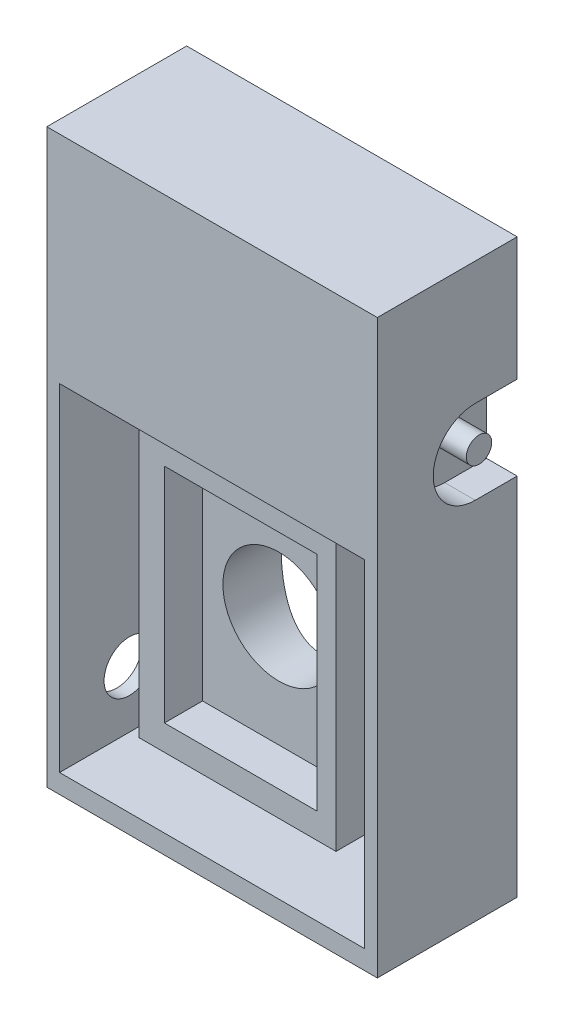
SolidWorks part; units mm, degrees
ref_plane "Front Plane" through (0, 0, 0) normal (0, 0, 1) x (1, 0, 0)
ref_plane "Top Plane" through (0, 0, 0) normal (0, 1, 0) x (1, 0, 0)
ref_plane "Right Plane" through (0, 0, 0) normal (1, 0, 0) x (0, 0, -1)
sketch "Sketch1" plane through (0, 0, 0) normal (0, 0, 1) x (1, 0, 0)
  line L1 (0, 0) -> (26, 0)
  line L2 (0, 0) -> (0, -45)
  line L3 (0, -45) -> (26, -45)
  line L4 (26, 0) -> (26, -45)
  dimension "D1" = 45
  dimension "D2" = 26
extrude "Boss-Extrude1" add sketch "Sketch1" along normal blind 11
sketch "Sketch2" plane through (0, -45, 0) normal (0, -1, 0) x (1, 0, 0)
  line L0 (0, 0) -> (26, 0) construction
  line L1 (7, 0) -> (19, 0) construction
  line L2 (13, 2.5) -> (13, 0) construction
  circle A0 centre (13, -5.95) radius 8.45
  point P5 (13, 0)
  dimension "D1" = 2.5
  dimension "D2" = 12
extrude "Cut-Extrude1" cut sketch "Sketch2" against normal blind 28
ref_plane "Plane1" through (0, -43.5, 0) normal (0, -1, 0) x (-1, 0, 0)
sketch "Sketch4" plane through (0, -43.5, 0) normal (0, -1, 0) x (-1, 0, 0)
  line L0 (-1, -11) -> (-1, -1)
  line L1 (-1, -1) -> (-6.5969, -1)
  line L2 (-19.4031, -1) -> (-25, -1)
  line L3 (-25, -1) -> (-25, -11)
  line L4 (-1, -11) -> (-25, -11)
  line L5 (0, 0) -> (-7, 0)
  line L6 (-19, 0) -> (-26, 0)
  line L7 (-26, 0) -> (-26, -11)
  line L8 (-26, -11) -> (0, -11)
  line L9 (0, -11) -> (0, 0)
  line L10 (0, 0) -> (-7, 0) construction
  line L11 (-19, 0) -> (-26, 0) construction
  line L12 (-26, 0) -> (-26, -11) construction
  line L13 (-26, -11) -> (0, -11) construction
  line L14 (0, -11) -> (0, 0) construction
  arc A0 (-19.4031, -1) -> (-6.5969, -1) centre (-13, 5.95) ccw
  arc A1 (-19, 0) -> (-7, 0) centre (-13, 5.95) ccw
  arc A2 (-19, 0) -> (-7, 0) centre (-13, 5.95) ccw construction
  dimension "D1" = 0
  dimension "D2" = 1
extrude "Cut-Extrude2" cut sketch "Sketch4" against normal blind 26.5
ref_plane "Plane2" through (0, 0, 3.5) normal (0, 0, 1) x (1, 0, 0)
sketch "Sketch5" plane through (0, -17, 0) normal (0, -1, 0) x (1, 0, 0)
  line L0 (6.5969, 1) -> (5.25, 1)
  line L1 (1, 1) -> (6.5969, 1) construction
  line L2 (5.25, 1) -> (5.25, 9)
  line L3 (5.25, 9) -> (20.75, 9)
  line L4 (20.75, 9) -> (20.75, 1)
  line L5 (19.4031, 1) -> (25, 1) construction
  line L6 (20.75, 1) -> (19.4031, 1)
  line L7 (25, 11) -> (1, 11) construction
  arc A0 (19.4031, 1) -> (6.5969, 1) centre (13, -5.95) ccw construction
  arc A1 (19.4031, 1) -> (6.5969, 1) centre (13, -5.95) ccw
  point P3 (13, 11)
  point P14 (13, 9)
  dimension "D1" = 8
  dimension "D2" = 15.5
extrude "Boss-Extrude2" add sketch "Sketch5" along normal blind 23
sketch "Sketch6" plane through (0, 0, 9) normal (0, 0, 1) x (1, 0, 0)
  line L0 (20.75, -40) -> (5.25, -40) construction
  line L1 (7.25, -38) -> (19.25, -38)
  line L2 (7.25, -38) -> (7.25, -20.5)
  line L3 (7.25, -20.5) -> (19.25, -20.5)
  line L4 (19.25, -38) -> (19.25, -20.5)
  line L5 (5.25, -40) -> (5.25, -17) construction
  dimension "D1" = 17.5
  dimension "D2" = 12
  dimension "D3" = 2
  dimension "D4" = 2
extrude "Cut-Extrude3" cut sketch "Sketch6" against normal blind 3
sketch "Sketch7" plane through (0, 0, 6) normal (0, 0, 1) x (1, 0, 0)
  line L0 (19.25, -20.5) -> (7.25, -20.5) construction
  line L1 (7.25, -20.5) -> (7.25, -38) construction
  circle A0 centre (13.25, -29.25) radius 4.4
  point P2 (0, 0)
  point P5 (13.25, -20.5)
  point P6 (0, 0)
  point P9 (7.25, -29.25)
  dimension "D1" = 8.8
extrude "Cut-Extrude4" cut sketch "Sketch7" against normal through all
sketch "Sketch8" plane through (0, 0, 0) normal (-1, 0, 0) x (0, 0, 1)
  line L0 (11, -45) -> (0, -45) construction
  circle A0 centre (5.5, -39) radius 2
  point P2 (0, 0)
  point P5 (5.5, -45)
  dimension "D2" = 4
  dimension "D1" = 6
extrude "Cut-Extrude5" cut sketch "Sketch8" against normal blind 3
sketch "Sketch9" plane through (0, 0, 0) normal (-1, 0, 0) x (0, 0, 1)
  line L6 (0, -16.3) -> (3.3, -16.3)
  line L7 (0, 0) -> (0, -45) construction
  line L8 (0, -9.7) -> (3.3, -9.7)
  line L9 (0, -16.3) -> (0, -9.7)
  arc A3 (3.3, -9.7) -> (3.3, -16.3) centre (3.3, -13) cw
  circle A4 centre (3, -13) radius 1
  point P11 (0, 0)
  point P12 (0, -13)
  dimension "D2" = 4
  dimension "D5" = 2
  dimension "D1" = 3.3
  dimension "D3" = 6.6
  dimension "D4" = 3
extrude "Cut-Extrude6" cut sketch "Sketch9" against normal blind 2.4
sketch "Sketch10" plane through (26, 0, 0) normal (1, 0, 0) x (0, 0, -1)
  line L3 (0, -16.3) -> (0, -9.7)
  line L4 (-3.3, -16.3) -> (0, -16.3)
  line L5 (0, -9.7) -> (-3.3, -9.7)
  line L6 (0, -16.3) -> (0, -9.7)
  line L7 (-3.3, -16.3) -> (0, -16.3)
  line L8 (0, -9.7) -> (-3.3, -9.7)
  arc A1 (-3.3, -9.7) -> (-3.3, -16.3) centre (-3.3, -13) ccw
  arc A2 (-3.3, -9.7) -> (-3.3, -16.3) centre (-3.3, -13) ccw
  circle A3 centre (-3, -13) radius 1
  circle A4 centre (-3, -13) radius 1
  dimension "D1" = 0
  dimension "D2" = 0
extrude "Cut-Extrude7" cut sketch "Sketch10" against normal blind 2.4
